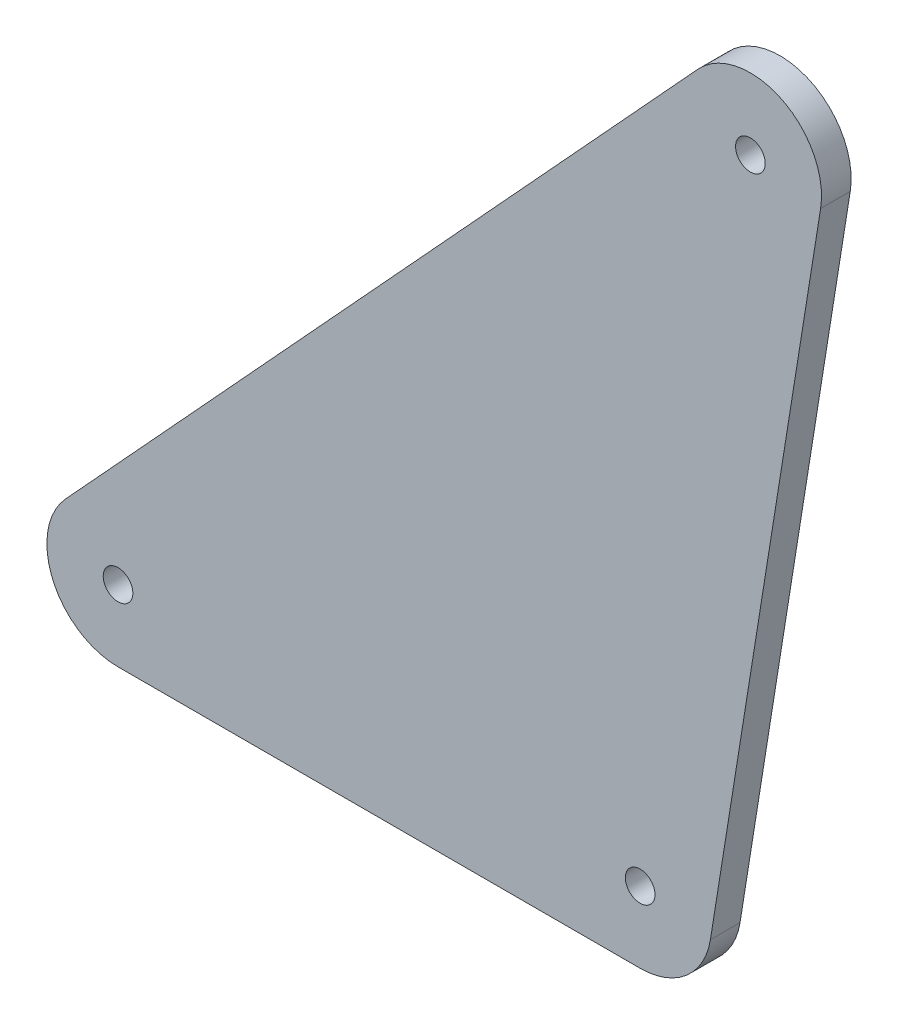
SolidWorks part; units mm, degrees
ref_plane "前视基准面" through (0, 0, 0) normal (0, 0, 1) x (1, 0, 0)
ref_plane "上视基准面" through (0, 0, 0) normal (0, 1, 0) x (1, 0, 0)
ref_plane "右视基准面" through (0, 0, 0) normal (1, 0, 0) x (0, 0, -1)
ref_plane "基准面4" through (0, 0, 5) normal (0, 0, 1) x (1, 0, 0)
sketch "草图1" plane through (0, 0, 5) normal (0, 0, 1) x (1, 0, 0)
  line L0 (0, -12) -> (88.08, -12)
  line L1 (99.9291, -1.8971) -> (118.5209, 114.2239)
  line L2 (97.8346, 124.2392) -> (-8.8372, 8.1181)
  circle A0 centre (88.08, 0) radius 2.5
  circle A1 centre (106.6718, 116.1211) radius 2.5
  circle A2 centre (0, 0) radius 2.5
  arc A3 (88.08, -12) -> (99.9291, -1.8971) centre (88.08, 0) ccw
  arc A4 (118.5209, 114.2239) -> (97.8346, 124.2392) centre (106.6718, 116.1211) ccw
  arc A5 (-8.8372, 8.1181) -> (0, -12) centre (0, 0) ccw
  dimension "D1" = 5
  dimension "D2" = 5
  dimension "D3" = 5
extrude "凸台-拉伸1" add sketch "草图1" against normal blind 5
